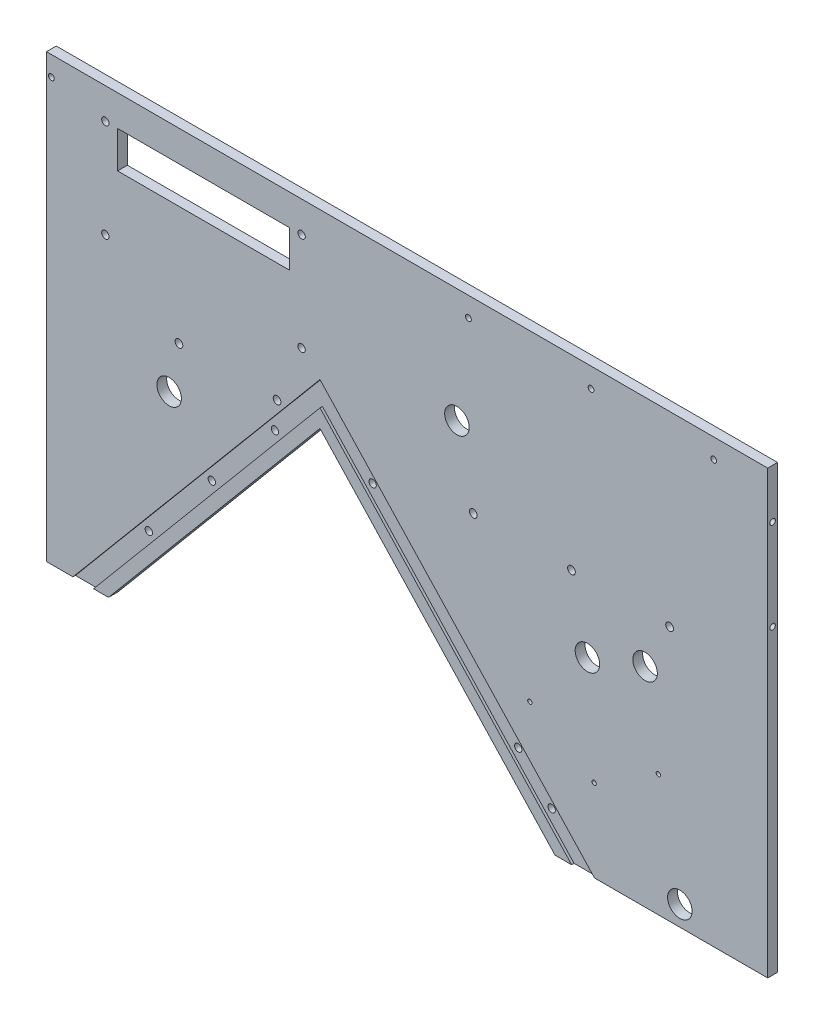
SolidWorks part; units mm, degrees
ref_plane "Front Plane" through (0, 0, 0) normal (0, 0, 1) x (1, 0, 0)
ref_plane "Top Plane" through (0, 0, 0) normal (0, 1, 0) x (1, 0, 0)
ref_plane "Right Plane" through (0, 0, 0) normal (1, 0, 0) x (0, 0, -1)
sketch "Sketch1" plane through (0, 0, 0) normal (0, 0, 1) x (1, 0, 0)
  line L0 (373.38, 127) -> (0, 127) construction
  line L1 (0, 0) -> (373.38, 0)
  line L2 (0, 0) -> (0, 228.6)
  line L3 (0, 228.6) -> (373.38, 228.6)
  line L4 (373.38, 0) -> (373.38, 228.6)
  line L5 (13.716, 228.6) -> (13.716, 0) construction
  line L6 (13.716, 0) -> (141.5948, 152.4)
  line L7 (141.5948, 152.4) -> (141.5948, 0)
  line L8 (141.5948, 0) -> (13.716, 0)
  line L9 (24.3726, 0) -> (141.5948, 139.7)
  line L10 (141.5948, 152.4) -> (141.5948, -50.8)
  line L11 (141.5948, -50.8) -> (331.0818, -50.8)
  line L12 (331.0818, -50.8) -> (141.5948, 152.4)
  line L13 (141.5948, 139.7) -> (319.2389, -50.8)
  dimension "D1" = 373.38
  dimension "D2" = 228.6
  dimension "D3" = 127
  dimension "D4" = 13.716
  dimension "D5" = 152.4
  dimension "D6" = 12.7
  dimension "D7" = 50
  dimension "D8" = 203.2
  dimension "D9" = 47
ref_plane "Plane1" through (0, 0, 0) normal (0, 0, 1) x (1, 0, 0)
sketch "Sketch2" plane through (0, 0, 0) normal (0, 0, 1) x (1, 0, 0)
  line L0 (32.1017, 0) -> (141.5948, 130.4888)
  line L1 (0, 228.6) -> (373.38, 228.6)
  line L2 (0, 228.6) -> (0, 0)
  line L3 (0, 0) -> (373.38, 0)
  line L4 (373.38, 228.6) -> (373.38, 0)
  line L5 (141.5948, 152.4) -> (141.5948, 0) construction
  line L6 (141.5948, 130.4888) -> (263.2776, 0)
  line L7 (263.2776, 0) -> (32.1017, 0)
  dimension "D1" = 50
  dimension "D2" = 47
extrude "Boss-Extrude1" add sketch "Sketch2" along normal blind 5.08 contours L0 L6 L3 L4 L1 L2
sketch "Sketch3" plane through (0, 0, 5.08) normal (0, 0, 1) x (1, 0, 0)
  line L0 (13.716, 0) -> (24.3726, 0)
  line L1 (24.3726, 0) -> (141.5948, 139.7)
  line L2 (141.5948, 139.7) -> (271.8671, 0)
  line L3 (0, 0) -> (373.38, 0) construction
  line L4 (141.5948, 139.7) -> (319.2389, -50.8) construction
  line L5 (271.8671, 0) -> (283.7101, 0)
  line L6 (331.0818, -50.8) -> (141.5948, 152.4) construction
  line L7 (283.7101, 0) -> (141.5948, 152.4)
  line L8 (141.5948, 152.4) -> (13.716, 0)
extrude "Cut-Extrude1" cut sketch "Sketch3" against normal blind 1.27
sketch "Sketch4" plane through (0, 0, 3.81) normal (0, 0, 1) x (1, 0, 0)
  line L0 (13.716, 0) -> (24.3726, 0) construction
  line L1 (24.3726, 0) -> (19.0443, 0) construction
  line L2 (19.0443, 0) -> (141.5948, 146.05) construction
  line L3 (141.5948, 152.4) -> (141.5948, 0) construction
  line L4 (13.716, 0) -> (141.5948, 152.4) construction
  line L5 (271.8671, 0) -> (283.7101, 0) construction
  line L6 (283.7101, 0) -> (277.7886, 0) construction
  line L7 (277.7886, 0) -> (141.5948, 146.05) construction
  circle A0 centre (51.6979, 38.9151) radius 1.905
  circle A1 centre (84.3515, 77.8301) radius 1.905
  circle A2 centre (117.0051, 116.7452) radius 1.905
  circle A3 centre (167.5789, 118.1854) radius 1.905
  circle A4 centre (242.9329, 37.3782) radius 1.905
  circle A5 centre (260.2557, 18.8018) radius 1.905
  dimension "D1" = 50.8
  dimension "D2" = 50.8
  dimension "D3" = 50.8
  dimension "D4" = 38.1
  dimension "D5" = 110.49
  dimension "D6" = 25.4
extrude "Cut-Extrude2" cut sketch "Sketch4" against normal blind 7.62
sketch "Sketch5" plane through (0, 0, 5.08) normal (0, 0, 1) x (1, 0, 0)
  line L0 (0, 0) -> (0, 228.6) construction
  line L1 (0, 228.6) -> (373.38, 228.6) construction
  line L3 (36.83, 212.598) -> (125.73, 212.598)
  line L4 (36.83, 212.598) -> (36.83, 193.548)
  line L5 (36.83, 193.548) -> (125.73, 193.548)
  line L6 (125.73, 212.598) -> (125.73, 193.548)
  circle A0 centre (30.48, 212.598) radius 1.905
  circle A1 centre (132.08, 212.598) radius 1.905
  circle A2 centre (30.48, 161.798) radius 1.905
  circle A3 centre (132.08, 161.798) radius 1.905
  dimension "D1" = 50.8
  dimension "D2" = 50.8
  dimension "D3" = 101.6
  dimension "D4" = 101.6
  dimension "D5" = 30.48
  dimension "D6" = 16.002
  dimension "D7" = 88.9
  dimension "D8" = 6.35
  dimension "D9" = 16.002
  dimension "D10" = 19.05
  dimension "D11" = 16.002
extrude "Cut-Extrude3" cut sketch "Sketch5" against normal blind 7.62
sketch "Sketch6" plane through (0, 0, 5.08) normal (0, 0, 1) x (1, 0, 0)
  line L0 (363.1301, 7.9412) -> (158.8009, 227.0574) construction
  line L1 (331.0818, -50.8) -> (141.5948, 152.4) construction
  line L2 (283.7101, 0) -> (337.4865, -53.7764)
  line L4 (373.38, 228.6) -> (391.16, 228.6) construction
  line L5 (391.16, 228.6) -> (391.16, -53.7764) construction
  line L6 (283.7101, 0) -> (373.38, 0) construction
  line L13 (283.7101, 0) -> (141.5948, 152.4) construction
  line L14 (373.38, 228.6) -> (373.38, 0) construction
  circle A0 centre (327.8861, 10.2843) radius 6.35
  circle A1 centre (280.0531, 97.0304) radius 6.35
  circle A2 centre (212.4943, 169.4783) radius 6.35
  circle A3 centre (327.8861, 10.2843) radius 63.5
  circle A4 centre (280.0531, 97.0304) radius 63.5
  circle A5 centre (212.4943, 169.4783) radius 63.5
  circle A6 centre (327.8861, 10.2843) radius 12.7
  dimension "D1" = 17.78
  dimension "D2" = 99.06
  dimension "D3" = 99.06
  dimension "D4" = 63.5
  dimension "D5" = 10.2843
  dimension "D6" = 45.4939
sketch "Sketch7" plane through (0, 0, 5.08) normal (0, 0, 1) x (1, 0, 0)
  line L0 (373.38, 0) -> (373.38, 228.6) construction
  line L1 (283.7101, 0) -> (373.38, 0) construction
  line L2 (0, 228.6) -> (0, 0) construction
  line L3 (0, 0) -> (13.716, 0) construction
  circle A0 centre (309.88, 107.95) radius 6.35
  circle A1 centre (63.5, 107.95) radius 6.35
  dimension "D1" = 63.5
  dimension "D3" = 63.5
  dimension "D2" = 107.95
  dimension "D4" = 107.95
extrude "Cut-Extrude5" cut sketch "Sketch7" against normal blind 7.62
sketch "Sketch8" plane through (0, 0, 5.08) normal (0, 0, 1) x (1, 0, 0)
  line L0 (0, 218.44) -> (373.38, 218.44) construction
  line L1 (0, 228.6) -> (0, 0) construction
  line L2 (373.38, 228.6) -> (373.38, 0) construction
  line L3 (0, 228.6) -> (373.38, 228.6) construction
  circle A0 centre (2.54, 218.44) radius 1.5
  circle A1 centre (218.44, 218.44) radius 1.5
  circle A2 centre (281.94, 218.44) radius 1.5
  circle A3 centre (345.44, 218.44) radius 1.5
  dimension "D2" = 2.54
  dimension "D1" = 10.16
  dimension "D3" = 215.9
  dimension "D4" = 63.5
  dimension "D5" = 63.5
extrude "Cut-Extrude6" cut sketch "Sketch8" against normal blind 25.4
sketch "Sketch9" plane through (0, 0, 5.08) normal (0, 0, 1) x (1, 0, 0)
  line L0 (0, 132.08) -> (373.38, 132.08) construction
  line L1 (0, 228.6) -> (0, 0) construction
  line L2 (373.38, 228.6) -> (373.38, 0) construction
  line L3 (0, 0) -> (13.716, 0) construction
  circle A0 centre (322.58, 132.08) radius 2
  circle A1 centre (271.78, 132.08) radius 2
  circle A2 centre (220.98, 132.08) radius 2
  circle A3 centre (119.38, 132.08) radius 2
  circle A4 centre (68.58, 132.08) radius 2
  dimension "D2" = 50.8
  dimension "D1" = 132.08
  dimension "D3" = 50.8
  dimension "D4" = 50.8
  dimension "D5" = 101.6
  dimension "D6" = 50.8
extrude "Cut-Extrude7" cut sketch "Sketch9" against normal blind 381
sketch "Sketch10" plane through (373.38, 0, 0) normal (1, 0, 0) x (0, 0, -1)
  line L0 (-2.54, 228.6) -> (-2.54, 0) construction
  line L1 (-5.08, 228.6) -> (0, 228.6) construction
  line L2 (-5.08, 0) -> (0, 0) construction
  circle A0 centre (-2.54, 203.2) radius 1.4224
  circle A1 centre (-2.54, 156.21) radius 1.4224
  dimension "D1" = 25.4
  dimension "D2" = 46.99
extrude "Cut-Extrude8" cut sketch "Sketch10" against normal blind 12.7
extrude "Cut-Extrude9" cut sketch "Sketch6" against normal blind 5.08 contours A2 | A1 | A0
sketch "Sketch11" plane through (0, 0, 0) normal (0, 0, -1) x (-1, 0, 0)
  circle A0 centre (-316.7597, 63.0887) radius 1.1303
  circle A2 centre (-250.247, 62.3403) radius 1.1303
  circle A3 centre (-283.5114, 42.6443) radius 1.1303
  dimension "D1" = 2.2606
  dimension "D2" = 2.2606
  dimension "D3" = 2.2606
extrude "Cut-Extrude10" cut sketch "Sketch11" against normal through all contours A0 | A3 | A2
